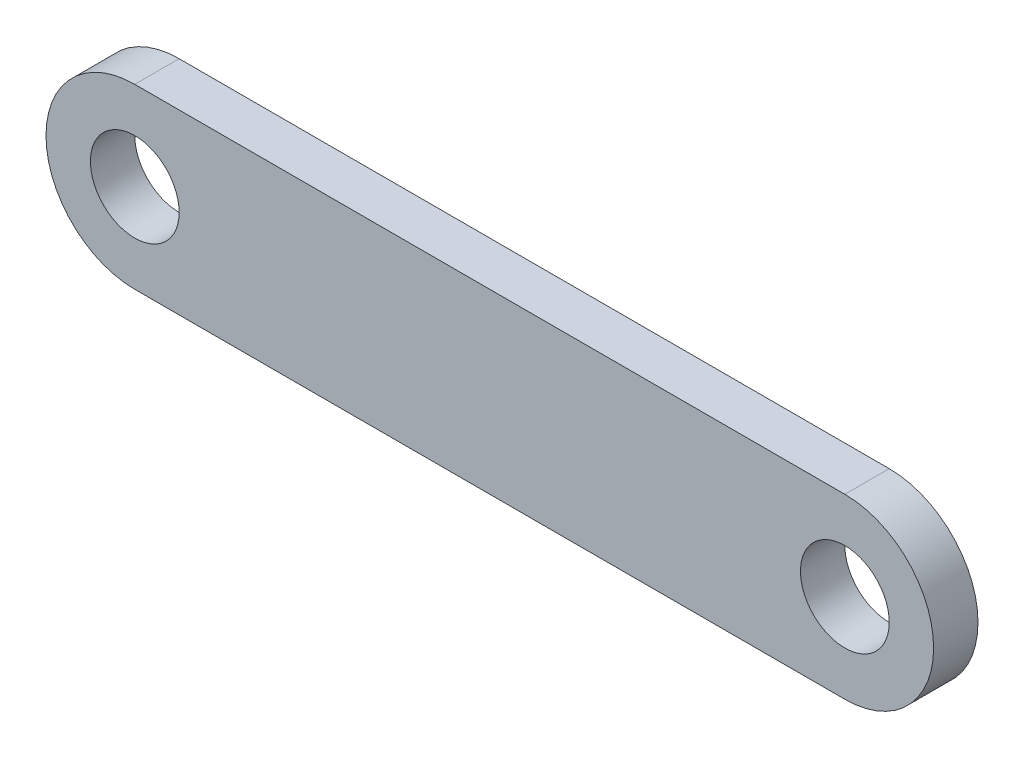
SolidWorks part; units mm, degrees
ref_plane "Front Plane" through (0, 0, 0) normal (0, 0, 1) x (1, 0, 0)
ref_plane "Top Plane" through (0, 0, 0) normal (0, 1, 0) x (1, 0, 0)
ref_plane "Right Plane" through (0, 0, 0) normal (1, 0, 0) x (0, 0, -1)
sketch "Sketch1" plane through (0, 0, 0) normal (0, 0, 1) x (1, 0, 0)
  line L0 (0, 0) -> (32, 0) construction
  line L1 (0, 4) -> (32, 4)
  line L2 (0, -4) -> (32, -4)
  arc A0 (0, 4) -> (0, -4) centre (0, 0) ccw
  arc A1 (32, -4) -> (32, 4) centre (32, 0) ccw
  circle A2 centre (0, 0) radius 2
  circle A3 centre (32, 0) radius 2
  point P3 (16, 0)
  point P12 (-4, 0)
  dimension "D1" = 32
  dimension "D2" = 4
  dimension "D3" = 4
  dimension "D4" = 4
extrude "Boss-Extrude1" add sketch "Sketch1" along normal mid plane 2
